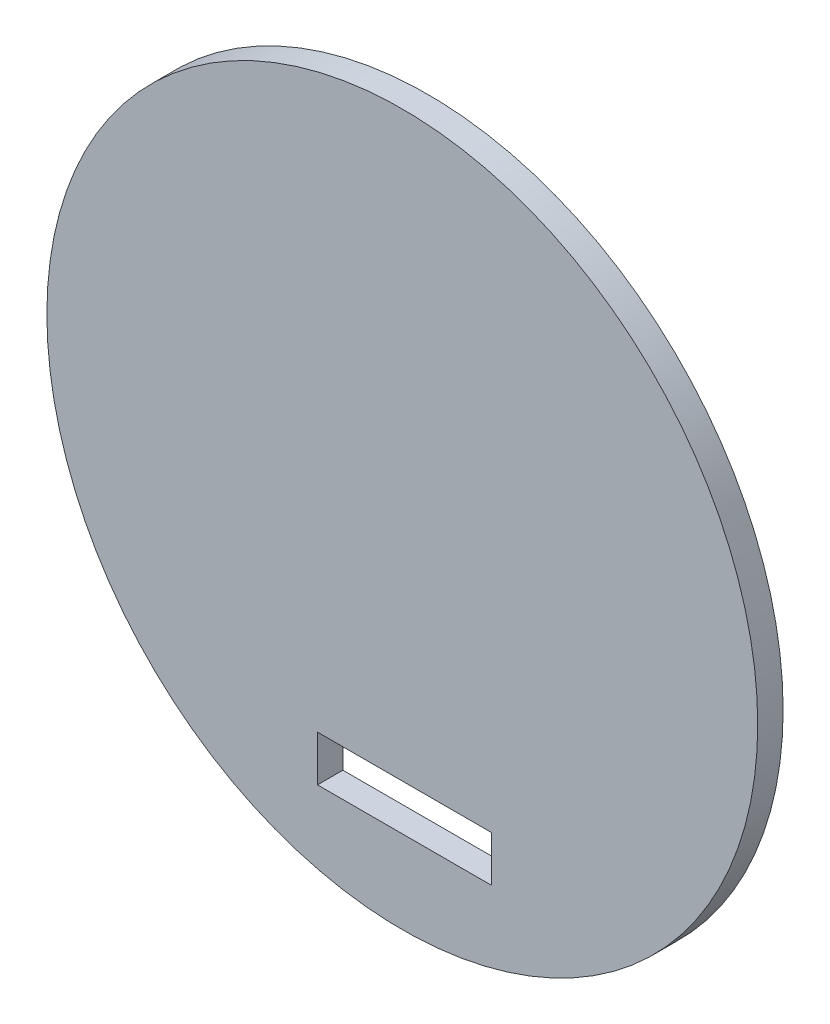
SolidWorks part; units mm, degrees
ref_plane "Front Plane" through (0, 0, 0) normal (0, 0, 1) x (1, 0, 0)
ref_plane "Top Plane" through (0, 0, 0) normal (0, 1, 0) x (1, 0, 0)
ref_plane "Right Plane" through (0, 0, 0) normal (1, 0, 0) x (0, 0, -1)
sketch "Sketch1" plane through (0, 0, 0) normal (0, 0, 1) x (1, 0, 0)
  line L1 (-3.3407, -8.9279) -> (3.5093, -8.9279)
  line L2 (-3.3407, -8.9279) -> (-3.3407, -10.7279)
  line L3 (-3.3407, -10.7279) -> (3.5093, -10.7279)
  line L4 (3.5093, -8.9279) -> (3.5093, -10.7279)
  circle A0 centre (0, 0) radius 14
  point P7 (-2.404, -11.0051)
  dimension "D1" = 28
  dimension "D2" = 6.85
  dimension "D3" = 1.8
extrude "Boss-Extrude4" add sketch "Sketch1" along normal blind 1 contours A0 | L2 L1 L4 L3
